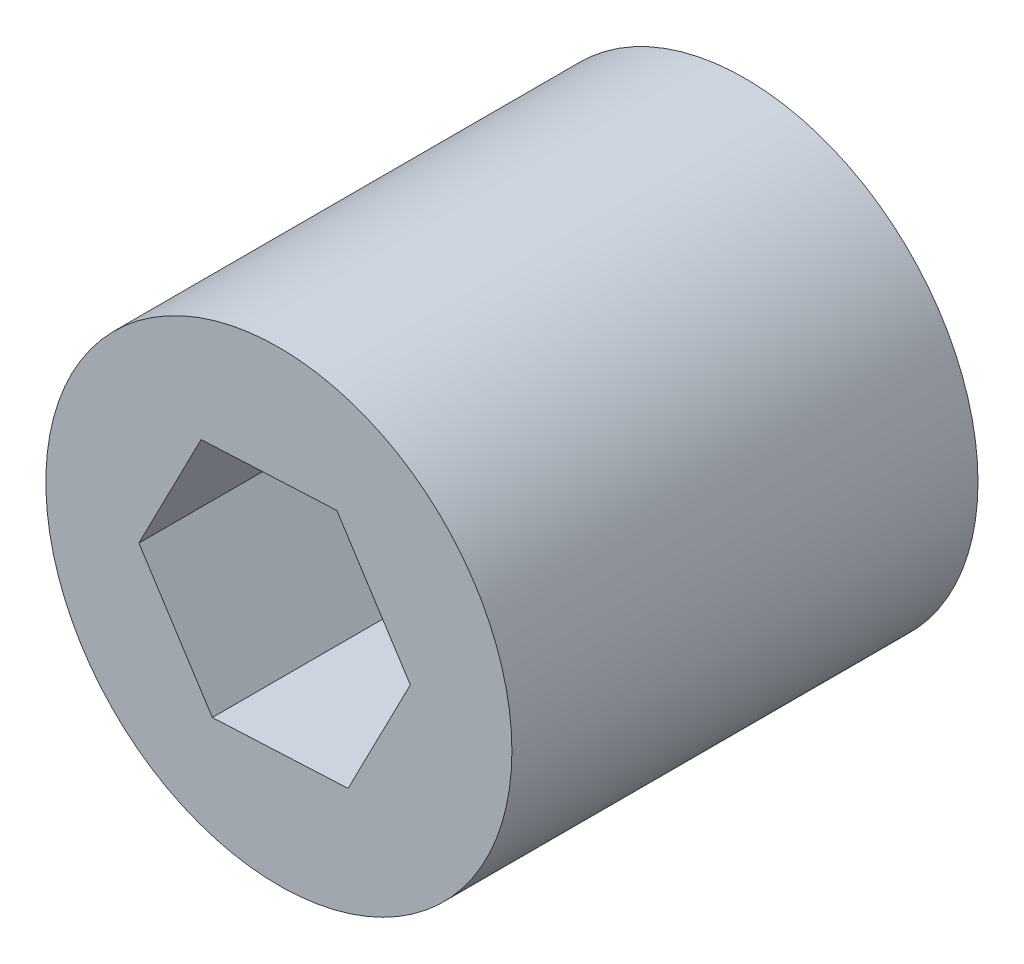
SolidWorks part; units mm, degrees
material "Rubber"
ref_plane "Front Plane" through (0, 0, 0) normal (0, 0, 1) x (1, 0, 0)
ref_plane "Top Plane" through (0, 0, 0) normal (0, 1, 0) x (1, 0, 0)
ref_plane "Right Plane" through (0, 0, 0) normal (1, 0, 0) x (0, 0, -1)
sketch "Sketch2" plane through (0, 0, 0) normal (0, 0, 1) x (1, 0, 0)
  line L1 (4.2627, -1.7784) -> (3.6715, 2.8024)
  line L2 (3.6715, 2.8024) -> (-0.5912, 4.5808)
  line L3 (-0.5912, 4.5808) -> (-4.2627, 1.7784)
  line L4 (-4.2627, 1.7784) -> (-3.6715, -2.8024)
  line L5 (-3.6715, -2.8024) -> (0.5912, -4.5808)
  line L6 (0.5912, -4.5808) -> (4.2627, -1.7784)
  line L7 (-3.6269, -6.5822) -> (3.7704, -6.2303)
  line L8 (3.7704, -6.2303) -> (7.1642, 0.352)
  line L9 (7.1642, 0.352) -> (3.1607, 6.5822)
  line L10 (3.1607, 6.5822) -> (-4.2366, 6.2303)
  line L11 (-4.2366, 6.2303) -> (-7.6304, -0.352)
  line L12 (-7.6304, -0.352) -> (-3.6269, -6.5822)
  circle A0 centre (0, 0) radius 12.7
  circle A1 centre (0, 0) radius 4 construction
  circle A2 centre (-0.2331, 0) radius 6.4135 construction
extrude "Boss-Extrude2" add sketch "Sketch2" along normal blind 25.4 contours A0 L12 L11 L10 L9 L8 L7 | L11 L12 L7 L8 L9 L10 L6 L5 L4 L3 L2 L1
